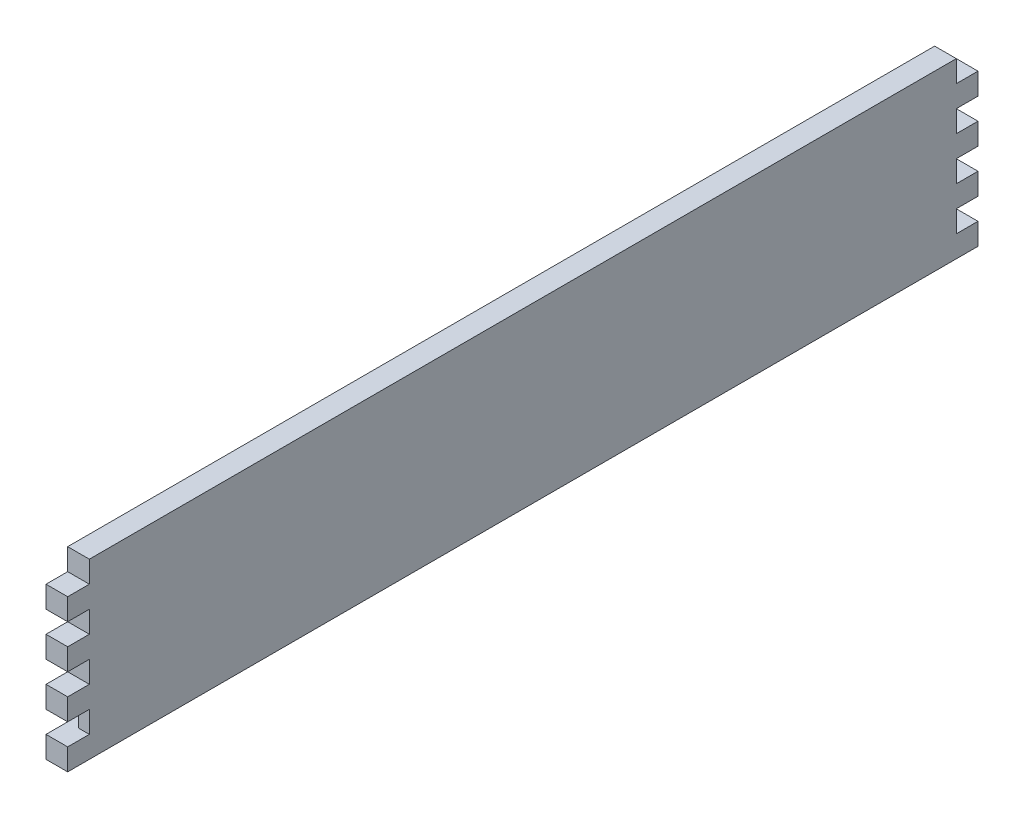
SolidWorks part; units mm, degrees
ref_plane "Front Plane" through (0, 0, 0) normal (0, 0, 1) x (1, 0, 0)
ref_plane "Top Plane" through (0, 0, 0) normal (0, 1, 0) x (1, 0, 0)
ref_plane "Right Plane" through (0, 0, 0) normal (1, 0, 0) x (0, 0, -1)
sketch "Sketch1" plane through (0, 0, 0) normal (1, 0, 0) x (0, 0, -1)
  line L0 (12.7, 101.6) -> (12.7, 88.9)
  line L1 (0, 0) -> (533.4, 0)
  line L2 (0, 0) -> (0, 12.7)
  line L3 (12.7, 101.6) -> (520.7, 101.6)
  line L4 (533.4, 0) -> (533.4, 12.7)
  line L5 (12.7, 88.9) -> (0, 88.9)
  line L6 (12.7, 76.2) -> (0, 76.2)
  line L8 (12.7, 63.5) -> (0, 63.5)
  line L9 (12.7, 76.2) -> (12.7, 63.5)
  line L10 (12.7, 50.8) -> (0, 50.8)
  line L12 (12.7, 38.1) -> (0, 38.1)
  line L13 (12.7, 50.8) -> (12.7, 38.1)
  line L14 (12.7, 25.4) -> (0, 25.4)
  line L16 (12.7, 12.7) -> (0, 12.7)
  line L17 (12.7, 25.4) -> (12.7, 12.7)
  line L18 (12.7, 0) -> (0, 0)
  line L20 (0, 76.2) -> (0, 88.9)
  line L21 (0, 50.8) -> (0, 63.5)
  line L22 (0, 25.4) -> (0, 38.1)
  line L23 (520.7, 101.6) -> (520.7, 88.9)
  line L24 (520.7, 88.9) -> (533.4, 88.9)
  line L26 (520.7, 76.2) -> (533.4, 76.2)
  line L27 (520.7, 76.2) -> (520.7, 63.5)
  line L28 (520.7, 63.5) -> (533.4, 63.5)
  line L30 (520.7, 50.8) -> (533.4, 50.8)
  line L31 (520.7, 50.8) -> (520.7, 38.1)
  line L32 (520.7, 38.1) -> (533.4, 38.1)
  line L34 (520.7, 25.4) -> (533.4, 25.4)
  line L35 (520.7, 25.4) -> (520.7, 12.7)
  line L36 (520.7, 12.7) -> (533.4, 12.7)
  line L38 (520.7, 0) -> (533.4, 0)
  line L39 (533.4, 76.2) -> (533.4, 88.9)
  line L40 (533.4, 50.8) -> (533.4, 63.5)
  line L41 (533.4, 25.4) -> (533.4, 38.1)
  line L42 (12.7, 88.9) -> (12.7, 76.2) [skipped]
  line L43 (12.7, 63.5) -> (12.7, 50.8) [skipped]
  line L44 (12.7, 38.1) -> (12.7, 25.4) [skipped]
  line L45 (12.7, 12.7) -> (12.7, 0) [skipped]
  line L46 (520.7, 88.9) -> (520.7, 76.2) [skipped]
  line L47 (520.7, 63.5) -> (520.7, 50.8) [skipped]
  line L48 (520.7, 38.1) -> (520.7, 25.4) [skipped]
  line L49 (520.7, 12.7) -> (520.7, 0) [skipped]
  dimension "D1" = 533.4
  dimension "D2" = 101.6
  dimension "D3" = 12.7
  dimension "D4" = 12.7
  dimension "D6" = 12.7
  dimension "D7" = 12.7
  dimension "D5" = 8
  dimension "D8" = 8
extrude "Boss-Extrude1" add sketch "Sketch1" along normal blind 12.7 contours L34 L41 L32 L31 L30 L40 L28 L27 L26 L39 L24 L23 L3 L0 L5 L20 L6 L9 L8 L21 L10 L13 L12 L22 L14 L17 L16 L2 L1 L4 L36 L35
sketch "Sketch2" plane through (0, 0, 0) normal (1, 0, 0) x (0, 0, -1)
  line L0 (0, 0) -> (533.4, 0) construction
  line L1 (541.6268, 19.05) -> (-15.4725, 19.05)
  line L2 (541.6268, 19.05) -> (541.6268, 12.7)
  line L3 (541.6268, 12.7) -> (-15.4725, 12.7)
  line L4 (-15.4725, 19.05) -> (-15.4725, 12.7)
  dimension "D1" = 6.35
  dimension "D2" = 12.7
extrude "Cut-Extrude1" cut sketch "Sketch2" along normal blind 6.35
